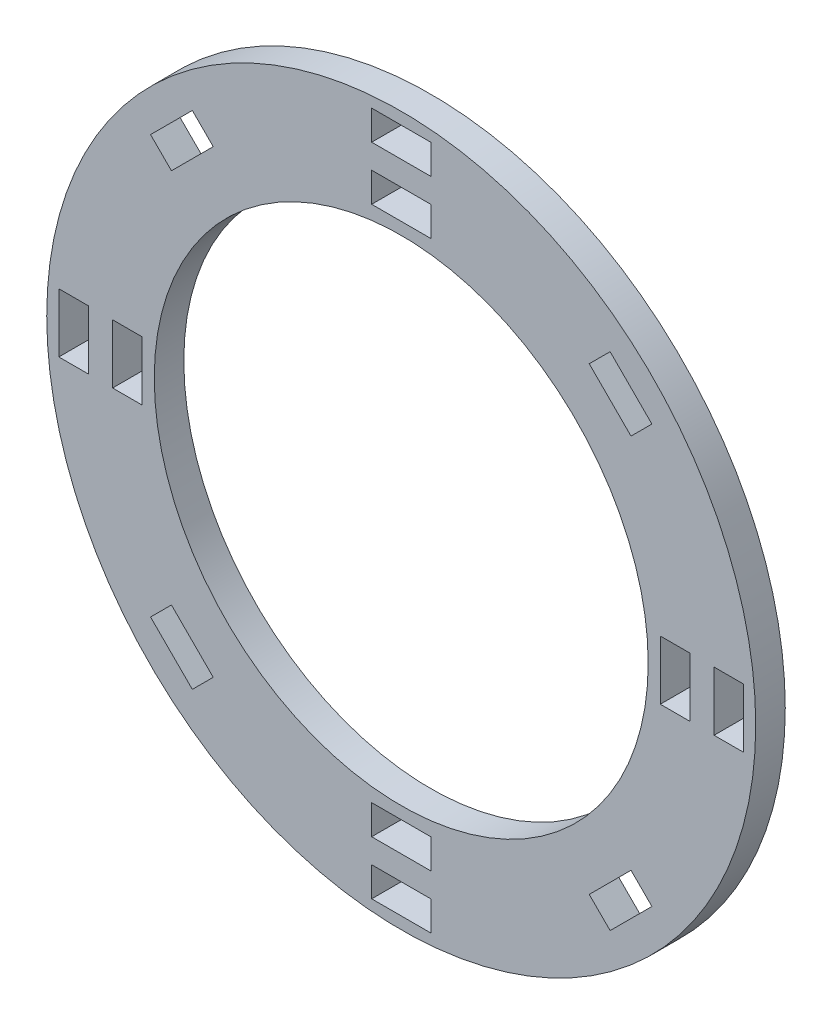
SolidWorks part; units mm, degrees
ref_plane "Front Plane" through (0, 0, 0) normal (0, 0, 1) x (1, 0, 0)
ref_plane "Top Plane" through (0, 0, 0) normal (0, 1, 0) x (1, 0, 0)
ref_plane "Right Plane" through (0, 0, 0) normal (1, 0, 0) x (0, 0, -1)
sketch "Sketch1" plane through (0, 0, 0) normal (0, 0, 1) x (1, 0, 0)
  circle A0 centre (0, 0) radius 53.086
  circle A5 centre (0, 0) radius 76.2
  point P23 (0, 0)
  dimension "D1" = 106.172
  dimension "D2" = 152.4
extrude "Boss-Extrude2" add sketch "Sketch1" along normal blind 6.35
sketch "Sketch2" plane through (0, 0, 6.35) normal (0, 0, 1) x (1, 0, 0)
  line L0 (0, 0) -> (0, 76.2) construction
  line L1 (-6.35, 73.5965) -> (6.35, 73.5965)
  line L2 (-6.35, 73.5965) -> (-6.35, 67.2465)
  line L3 (-6.35, 67.2465) -> (6.35, 67.2465)
  line L4 (6.35, 73.5965) -> (6.35, 67.2465)
  line L5 (-6.35, 62.0395) -> (6.35, 62.0395)
  line L6 (-6.35, 62.0395) -> (-6.35, 55.6895)
  line L7 (-6.35, 55.6895) -> (6.35, 55.6895)
  line L8 (6.35, 62.0395) -> (6.35, 55.6895)
  line L9 (0, 64.643) -> (0, 53.086) construction
  line L10 (-6.35, 62.0395) -> (6.35, 55.6895) construction
  line L11 (0, 76.2) -> (0, 64.643) construction
  line L12 (-6.35, 73.5965) -> (6.35, 67.2465) construction
  circle A0 centre (0, 0) radius 64.643 construction
  circle A1 centre (0, 0) radius 76.2 construction
  circle A2 centre (0, 0) radius 53.086 construction
  circle A3 centre (0, 0) radius 76.2 construction
  circle A4 centre (0, 0) radius 53.086 construction
  point P20 (0, 58.8645)
  point P21 (0, 58.8645)
  point P22 (0, 70.4215)
  point P23 (0, 70.4215)
  dimension "D5" = 129.286
  dimension "D6" = 152.4
  dimension "D7" = 106.172
  dimension "D1" = 6.35
  dimension "D2" = 12.7
  dimension "D3" = 6.35
  dimension "D4" = 12.7
extrude "Cut-Extrude1" cut sketch "Sketch2" against normal up to next
pattern_circular "CirPattern1" count 4 over 360 about axis through (0, 0, 0) along (0, 0, 1) of "Cut-Extrude1"
sketch "Sketch3" plane through (0, 0, 6.35) normal (0, 0, 1) x (1, 0, 0)
  line L0 (0, 0) -> (53.8815, 53.8815) construction
  line L1 (40.4112, 49.3914) -> (44.9013, 53.8815)
  line L2 (44.9013, 53.8815) -> (53.8815, 44.9013)
  line L3 (53.8815, 44.9013) -> (49.3914, 40.4112)
  line L4 (49.3914, 40.4112) -> (40.4112, 49.3914)
  circle A0 centre (0, 0) radius 76.2 construction
  circle A1 centre (0, 0) radius 53.086 construction
  point P9 (37.241, 51.3016)
  point P12 (49.3914, 49.3914)
  point P13 (44.9013, 53.8815)
  point P14 (41.0092, 51.1749)
  dimension "D1" = 45
  dimension "D2" = 63.5
  dimension "D3" = 6.35
  dimension "D4" = 12.7
extrude "Spacer Holes" cut sketch "Sketch3" against normal up to next
pattern_circular "CirPattern2" count 4 over 360 about axis through (0, 0, 0) along (0, 0, 1) of "Spacer Holes"
equation "\"D5@Sketch2\"=(\"D6@Sketch2\"+\"D7@Sketch2\")/2"
